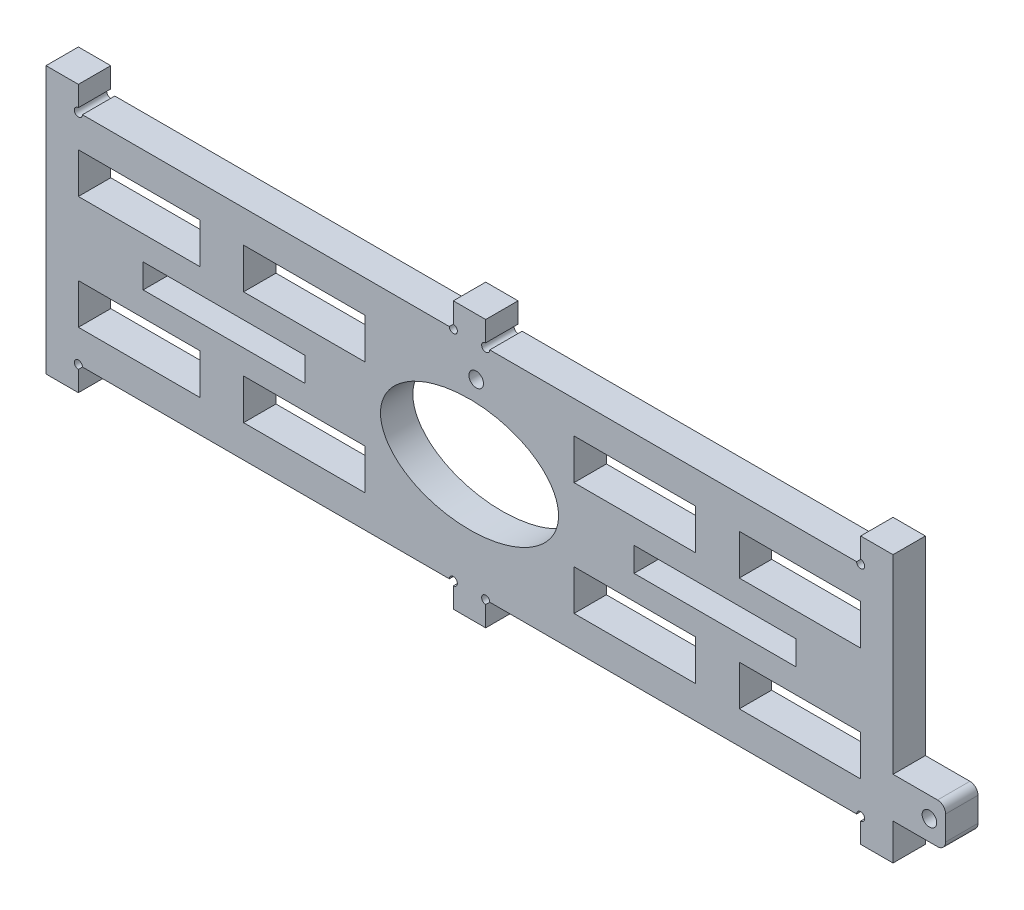
SolidWorks part; units mm, degrees
ref_plane "前视基准面" through (0, 0, 0) normal (0, 0, 1) x (1, 0, 0)
ref_plane "上视基准面" through (0, 0, 0) normal (0, 1, 0) x (1, 0, 0)
ref_plane "右视基准面" through (0, 0, 0) normal (1, 0, 0) x (0, 0, -1)
sketch "草图2" plane through (0, 0, 0) normal (0, 0, 1) x (1, 0, 0)
  line L0 (92.36, 3) -> (46.93, 3)
  line L1 (46.43, 0) -> (46.43, 2.5)
  line L2 (42.43, 0) -> (46.43, 0)
  line L3 (42.43, 0) -> (42.43, 2.5)
  line L4 (41.93, 3) -> (-3.5, 3)
  line L5 (-4, 0) -> (-4, 2.5)
  line L6 (-8, 0) -> (-4, 0)
  line L7 (-8, 35) -> (-8, 0)
  line L8 (92.86, 0) -> (92.86, 2.5)
  line L9 (96.86, 0) -> (92.86, 0)
  line L10 (96.86, 35) -> (96.86, 0)
  line L11 (92.36, 32) -> (46.93, 32)
  line L12 (46.43, 35) -> (46.43, 32.5)
  line L13 (42.43, 35) -> (46.43, 35)
  line L14 (42.43, 35) -> (42.43, 32.5)
  line L15 (41.93, 32) -> (-3.5, 32)
  line L16 (-4, 35) -> (-4, 32.5)
  line L17 (-8, 35) -> (-4, 35)
  line L18 (92.86, 35) -> (92.86, 32.5)
  line L19 (96.86, 35) -> (92.86, 35)
  arc A0 (46.93, 3) -> (46.43, 2.5) centre (46.43, 3) ccw
  arc A1 (42.43, 2.5) -> (41.93, 3) centre (42.43, 3) ccw
  arc A2 (-3.5, 3) -> (-4, 2.5) centre (-4, 3) ccw
  arc A3 (92.86, 2.5) -> (92.36, 3) centre (92.86, 3) ccw
  arc A4 (46.43, 32.5) -> (46.93, 32) centre (46.43, 32) ccw
  arc A5 (41.93, 32) -> (42.43, 32.5) centre (42.43, 32) ccw
  arc A6 (-4, 32.5) -> (-3.5, 32) centre (-4, 32) ccw
  arc A7 (92.36, 32) -> (92.86, 32.5) centre (92.86, 32) ccw
extrude "凸台-拉伸2" add sketch "草图2" along normal blind 4
ref_plane "基准面3" through (48.43, 0, 0) normal (1, 0, 0) x (0, 0, -1)
split "分割1" trim tools "基准面3" bodies to split 110 resulting bodies 111 112
move or copy body "实体-移动/复制1" bodies to move or copy 111 copy no translate (-0.1, 0, 0)
ref_plane "基准面4" through (40.43, 0, 0) normal (-1, 0, 0) x (0, 0, 1)
split "分割2" trim tools "基准面4" bodies to split 112 resulting bodies 114 115
move or copy body "实体-移动/复制2" bodies to move or copy 114 copy no translate (0.1, 0, 0)
combine bodies "组合2" operation type add bodies to combine 113 115 116
ref_plane "基准面5" through (0, 27, 0) normal (0, 1, 0) x (1, 0, 0)
split "分割3" trim tools "基准面5" bodies to split 118 resulting bodies 119 120
move or copy body "实体-移动/复制3" bodies to move or copy 119 copy no translate (0, -2, 0)
combine bodies "组合3" operation type add bodies to combine 121 120
sketch "草图3" plane through (0, 0, 0) normal (0, 0, -1) x (-1, 0, 0)
  line L0 (-96.76, 16.5) -> (32.0869, 16.5) construction
  line L1 (-96.76, 0) -> (-96.76, 33) construction
  line L3 (-102.26, 9.5) -> (-96.76, 9.5)
  line L4 (-103.26, 8.5) -> (-103.26, 5.5)
  line L5 (-102.26, 4.5) -> (-96.76, 4.5)
  line L6 (-96.76, 9.5) -> (-96.76, 4.5)
  circle A1 centre (-101.26, 7) radius 0.9
  arc A2 (-102.26, 4.5) -> (-103.26, 5.5) centre (-102.26, 5.5) cw
  arc A3 (-103.26, 8.5) -> (-102.26, 9.5) centre (-102.26, 8.5) cw
  point P16 (-103.26, 9.5)
  dimension "D3" = 14
  dimension "D4" = 1.8
  dimension "D5" = 2
  dimension "D6" = 2.5
  dimension "D7" = 1
  dimension "D1" = 6.5
  dimension "D2" = 5
extrude "凸台-拉伸3" add sketch "草图3" against normal blind 4
sketch "草图4" plane through (0, 0, 0) normal (0, 0, -1) x (-1, 0, 0)
  circle A0 centre (-45.26, 26) radius 0.9
  circle A1 centre (-101.26, 7) radius 0.9 construction
  dimension "D1" = 1.8
  dimension "D2" = 19
  dimension "D3" = 56
extrude "切除-拉伸1" cut sketch "草图4" against normal blind 10
sketch "草图5" plane through (0, 0, 0) normal (0, 0, -1) x (-1, 0, 0)
  line L0 (-69.595, 30) -> (-69.595, 3) construction
  line L1 (-92.76, 26) -> (-77.76, 26)
  line L2 (-92.76, 26) -> (-92.76, 21)
  line L3 (-92.76, 21) -> (-77.76, 21)
  line L4 (-77.76, 26) -> (-77.76, 21)
  line L5 (-92.26, 30) -> (-46.93, 30) construction
  line L6 (-46.93, 3) -> (-92.26, 3) construction
  line L7 (-69.595, 16.5) -> (-40.2022, 16.5) construction
  line L8 (-96.76, 9.5) -> (-96.76, 33) construction
  line L9 (-72.345, 26) -> (-57.345, 26)
  line L10 (-72.345, 26) -> (-72.345, 21)
  line L11 (-72.345, 21) -> (-57.345, 21)
  line L12 (-57.345, 26) -> (-57.345, 21)
  line L17 (-31.515, 26) -> (-16.515, 26)
  line L18 (-31.515, 26) -> (-31.515, 21)
  line L19 (-31.515, 21) -> (-16.515, 21)
  line L20 (-16.515, 26) -> (-16.515, 21)
  line L21 (-11.1, 26) -> (3.9, 26)
  line L22 (-11.1, 26) -> (-11.1, 21)
  line L23 (-11.1, 21) -> (3.9, 21)
  line L24 (3.9, 26) -> (3.9, 21)
  line L25 (7.9, 33) -> (7.9, 0) construction
  line L26 (-51.93, 26) -> (-36.93, 26) [skipped]
  line L27 (-51.93, 26) -> (-51.93, 21) [skipped]
  line L28 (-51.93, 21) -> (-36.93, 21) [skipped]
  line L29 (-36.93, 26) -> (-36.93, 21) [skipped]
  line L30 (3.9, 7) -> (3.9, 12)
  line L31 (-11.1, 12) -> (3.9, 12)
  line L32 (-11.1, 7) -> (-11.1, 12)
  line L33 (-11.1, 7) -> (3.9, 7)
  line L34 (-16.515, 7) -> (-16.515, 12)
  line L35 (-31.515, 12) -> (-16.515, 12)
  line L36 (-31.515, 7) -> (-31.515, 12)
  line L37 (-31.515, 7) -> (-16.515, 7)
  line L38 (-57.345, 7) -> (-57.345, 12)
  line L39 (-72.345, 12) -> (-57.345, 12)
  line L40 (-72.345, 7) -> (-72.345, 12)
  line L41 (-72.345, 7) -> (-57.345, 7)
  line L42 (-77.76, 7) -> (-77.76, 12)
  line L43 (-92.76, 12) -> (-77.76, 12)
  line L44 (-92.76, 7) -> (-92.76, 12)
  line L45 (-92.76, 7) -> (-77.76, 7)
  line L51 (-44.43, 0) -> (-44.43, 33) construction
  line L52 (-84.76, 18) -> (-64.76, 18)
  line L53 (-84.76, 18) -> (-84.76, 15)
  line L54 (-84.76, 15) -> (-64.76, 15)
  line L55 (-64.76, 18) -> (-64.76, 15)
  line L56 (-42.43, 0) -> (-46.43, 0) construction
  line L57 (-46.43, 33) -> (-42.43, 33) construction
  line L58 (-24.1, 18) -> (-24.1, 15)
  line L59 (-4.1, 15) -> (-24.1, 15)
  line L60 (-4.1, 18) -> (-4.1, 15)
  line L61 (-4.1, 18) -> (-24.1, 18)
  ellipse E0 centre (-44.43, 16.5) end of major axis (-33.43, 16.5) minor radius 7
  point P62 (-74.76, 18)
  dimension "D7" = 22
  dimension "D1" = 15
  dimension "D2" = 5
  dimension "D3" = 4
  dimension "D4" = 4
  dimension "D6" = 4
  dimension "D8" = 14
  dimension "D11" = 3
  dimension "D12" = 3
  dimension "D13" = 20
  dimension "D14" = 3
  dimension "D15" = 5.415
  dimension "D5" = 5
extrude "切除-拉伸2" cut sketch "草图5" against normal blind 10
